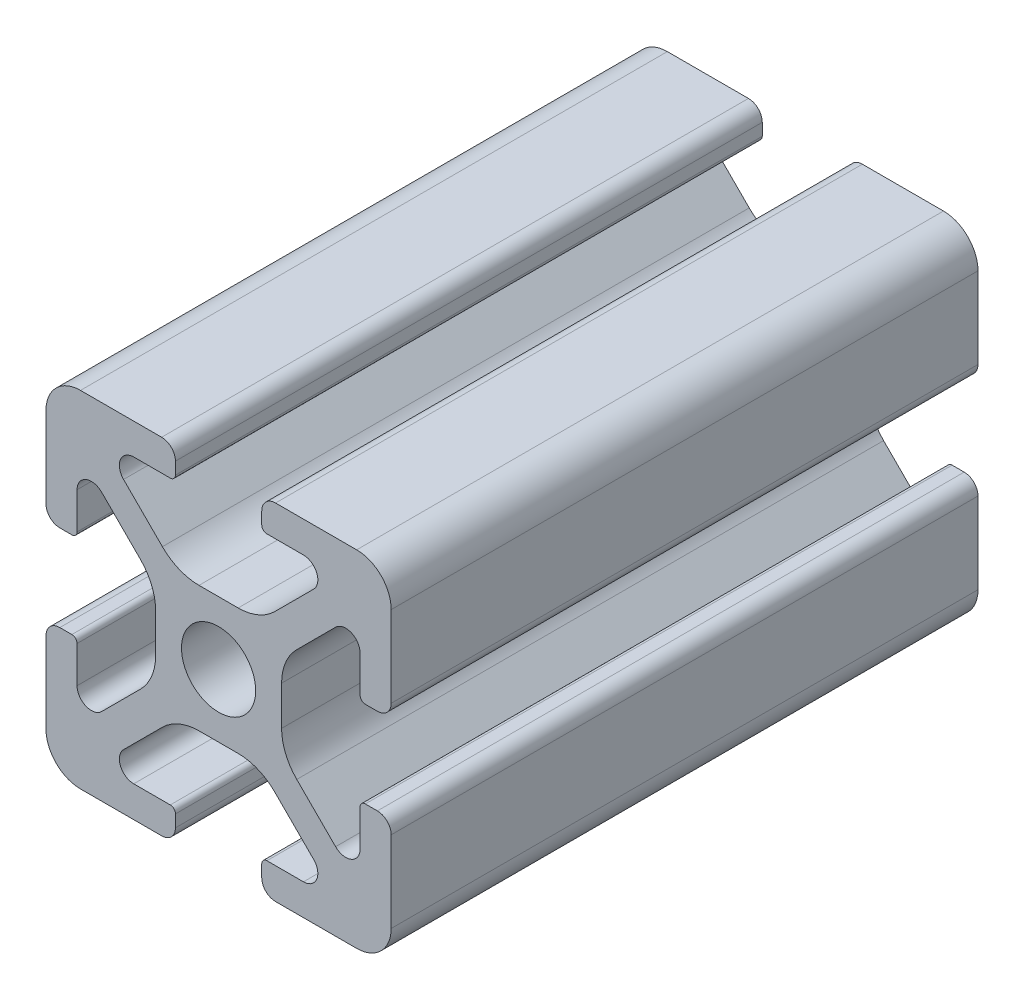
SolidWorks part; units mm, degrees
material "3.0205 (EN-AW 1200)"
ref_plane "Plan de face" through (0, 0, 0) normal (0, 0, 1) x (1, 0, 0)
ref_plane "Plan de dessus" through (0, 0, 0) normal (0, 1, 0) x (1, 0, 0)
ref_plane "Plan de droite" through (0, 0, 0) normal (1, 0, 0) x (0, 0, -1)
ref_plane "Plan1" through (0, 0, 0) normal (0, 0, -1) x (-1, 0, 0)
sketch "Esquisse1" plane through (0, 0, 0) normal (0, 0, -1) x (-1, 0, 0)
  line L0 (-12.5, 0.8) -> (-12.5, 1.5)
  line L1 (-12.8, 1.8) -> (-14.9176, 1.8)
  line L2 (-15.5062, 3.221) -> (-13.2559, 5.4713)
  line L3 (-11.1346, 6.35) -> (-8.8654, 6.35)
  line L4 (-6.7441, 5.4713) -> (-4.4938, 3.221)
  line L5 (-5.0824, 1.8) -> (-7.2, 1.8)
  line L6 (-7.5, 1.5) -> (-7.5, 0.8)
  line L7 (-6.7, 0) -> (-2, 0)
  line L8 (0, 2) -> (0, 6.7)
  line L9 (-0.8, 7.5) -> (-1.5, 7.5)
  line L10 (-1.8, 7.2) -> (-1.8, 5.0824)
  line L11 (-3.221, 4.4938) -> (-5.4713, 6.7441)
  line L12 (-6.35, 8.8654) -> (-6.35, 11.1346)
  line L13 (-5.4713, 13.2559) -> (-3.221, 15.5062)
  line L14 (-1.8, 14.9176) -> (-1.8, 12.8)
  line L15 (-1.5, 12.5) -> (-0.8, 12.5)
  line L16 (0, 13.3) -> (0, 18)
  line L17 (-2, 20) -> (-6.7, 20)
  line L18 (-7.5, 19.2) -> (-7.5, 18.5)
  line L19 (-7.2, 18.2) -> (-5.0824, 18.2)
  line L20 (-4.4938, 16.779) -> (-6.7441, 14.5287)
  line L21 (-8.8654, 13.65) -> (-11.1346, 13.65)
  line L22 (-13.2559, 14.5287) -> (-15.5062, 16.779)
  line L23 (-14.9176, 18.2) -> (-12.8, 18.2)
  line L24 (-12.5, 18.5) -> (-12.5, 19.2)
  line L25 (-13.3, 20) -> (-18, 20)
  line L26 (-20, 18) -> (-20, 13.3)
  line L27 (-19.2, 12.5) -> (-18.5, 12.5)
  line L28 (-18.2, 12.8) -> (-18.2, 14.9176)
  line L29 (-16.779, 15.5062) -> (-14.5287, 13.2559)
  line L30 (-13.65, 11.1346) -> (-13.65, 8.8654)
  line L31 (-14.5287, 6.7441) -> (-16.779, 4.4938)
  line L32 (-18.2, 5.0824) -> (-18.2, 7.2)
  line L33 (-18.5, 7.5) -> (-19.2, 7.5)
  line L34 (-20, 6.7) -> (-20, 2)
  line L35 (-18, 0) -> (-13.3, 0)
  arc A0 (-12.5, 1.5) -> (-12.8, 1.8) centre (-12.8, 1.5) ccw
  arc A1 (-14.9176, 1.8) -> (-15.5062, 3.221) centre (-14.9176, 2.6324) cw
  arc A2 (-13.2559, 5.4713) -> (-11.1346, 6.35) centre (-11.1346, 3.35) cw
  arc A3 (-8.8654, 6.35) -> (-6.7441, 5.4713) centre (-8.8654, 3.35) cw
  arc A4 (-4.4938, 3.221) -> (-5.0824, 1.8) centre (-5.0824, 2.6324) cw
  arc A5 (-7.2, 1.8) -> (-7.5, 1.5) centre (-7.2, 1.5) ccw
  arc A6 (-7.5, 0.8) -> (-6.7, 0) centre (-6.7, 0.8) ccw
  arc A7 (-2, 0) -> (0, 2) centre (-2, 2) ccw
  arc A8 (0, 6.7) -> (-0.8, 7.5) centre (-0.8, 6.7) ccw
  arc A9 (-1.5, 7.5) -> (-1.8, 7.2) centre (-1.5, 7.2) ccw
  arc A10 (-1.8, 5.0824) -> (-3.221, 4.4938) centre (-2.6324, 5.0824) cw
  arc A11 (-5.4713, 6.7441) -> (-6.35, 8.8654) centre (-3.35, 8.8654) cw
  arc A12 (-6.35, 11.1346) -> (-5.4713, 13.2559) centre (-3.35, 11.1346) cw
  arc A13 (-3.221, 15.5062) -> (-1.8, 14.9176) centre (-2.6324, 14.9176) cw
  arc A14 (-1.8, 12.8) -> (-1.5, 12.5) centre (-1.5, 12.8) ccw
  arc A15 (-0.8, 12.5) -> (0, 13.3) centre (-0.8, 13.3) ccw
  arc A16 (0, 18) -> (-2, 20) centre (-2, 18) ccw
  arc A17 (-6.7, 20) -> (-7.5, 19.2) centre (-6.7, 19.2) ccw
  arc A18 (-7.5, 18.5) -> (-7.2, 18.2) centre (-7.2, 18.5) ccw
  arc A19 (-5.0824, 18.2) -> (-4.4938, 16.779) centre (-5.0824, 17.3676) cw
  arc A20 (-6.7441, 14.5287) -> (-8.8654, 13.65) centre (-8.8654, 16.65) cw
  arc A21 (-11.1346, 13.65) -> (-13.2559, 14.5287) centre (-11.1346, 16.65) cw
  arc A22 (-15.5062, 16.779) -> (-14.9176, 18.2) centre (-14.9176, 17.3676) cw
  arc A23 (-12.8, 18.2) -> (-12.5, 18.5) centre (-12.8, 18.5) ccw
  arc A24 (-12.5, 19.2) -> (-13.3, 20) centre (-13.3, 19.2) ccw
  arc A25 (-18, 20) -> (-20, 18) centre (-18, 18) ccw
  arc A26 (-20, 13.3) -> (-19.2, 12.5) centre (-19.2, 13.3) ccw
  arc A27 (-18.5, 12.5) -> (-18.2, 12.8) centre (-18.5, 12.8) ccw
  arc A28 (-18.2, 14.9176) -> (-16.779, 15.5062) centre (-17.3676, 14.9176) cw
  arc A29 (-14.5287, 13.2559) -> (-13.65, 11.1346) centre (-16.65, 11.1346) cw
  arc A30 (-13.65, 8.8654) -> (-14.5287, 6.7441) centre (-16.65, 8.8654) cw
  arc A31 (-16.779, 4.4938) -> (-18.2, 5.0824) centre (-17.3676, 5.0824) cw
  arc A32 (-18.2, 7.2) -> (-18.5, 7.5) centre (-18.5, 7.2) ccw
  arc A33 (-19.2, 7.5) -> (-20, 6.7) centre (-19.2, 6.7) ccw
  arc A34 (-20, 2) -> (-18, 0) centre (-18, 2) ccw
  arc A35 (-13.3, 0) -> (-12.5, 0.8) centre (-13.3, 0.8) ccw
  circle A36 centre (-10, 10) radius 2.15
extrude "Boss.-Extru.1" add sketch "Esquisse1" against normal blind 34
